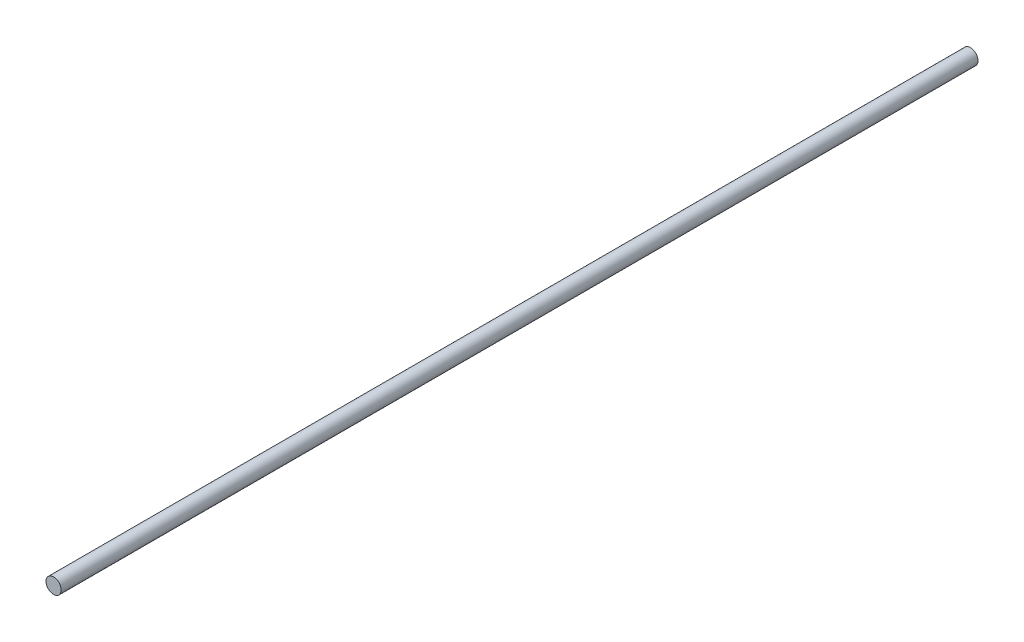
SolidWorks part; units mm, degrees
ref_plane "Front Plane" through (0, 0, 0) normal (0, 0, 1) x (1, 0, 0)
ref_plane "Top Plane" through (0, 0, 0) normal (0, 1, 0) x (1, 0, 0)
ref_plane "Right Plane" through (0, 0, 0) normal (1, 0, 0) x (0, 0, -1)
sketch "Sketch1" plane through (0, 0, 0) normal (0, 0, 1) x (1, 0, 0)
  circle A0 centre (0, 0) radius 1.7
  dimension "D1" = 3.4
extrude "Boss-Extrude1" add sketch "Sketch1" along normal mid plane 205
